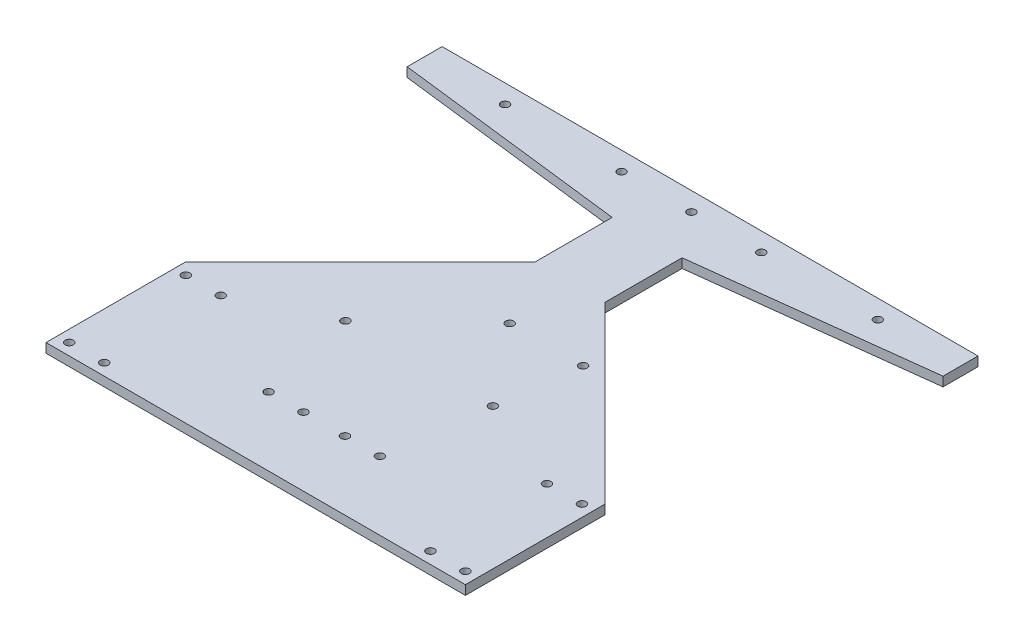
SolidWorks part; units mm, degrees
ref_plane "Front Plane" through (0, 0, 0) normal (0, 0, 1) x (1, 0, 0)
ref_plane "Top Plane" through (0, 0, 0) normal (0, 1, 0) x (1, 0, 0)
ref_plane "Right Plane" through (0, 0, 0) normal (1, 0, 0) x (0, 0, -1)
sketch "Sketch1" plane through (0, 0, 0) normal (0, 1, 0) x (1, 0, 0)
  line L0 (-90, 30) -> (-15, 105)
  line L2 (-90, 30) -> (-90, -30)
  line L3 (-90, -30) -> (90, -30)
  line L4 (90, 30) -> (90, -30)
  line L5 (-90, 30) -> (90, -30) construction
  line L6 (-90, -30) -> (90, 30) construction
  line L7 (90, 30) -> (15, 105)
  line L8 (15, 105) -> (15, 138)
  line L9 (15, 138) -> (115, 150)
  line L10 (115, 150) -> (115, 165)
  line L11 (115, 165) -> (-115, 165)
  line L12 (-115, 165) -> (-115, 150)
  line L13 (-115, 150) -> (-15, 138)
  line L14 (-15, 138) -> (-15, 105)
  line L15 (0, -55) -> (0, 55) construction
  line L16 (-55, 0) -> (55, 0) construction
  point P0 (0, 0)
  dimension "D1" = 60
  dimension "D2" = 180
  dimension "D3" = 100
  dimension "D4" = 15
  dimension "D5" = 15
  dimension "D6" = 15
  dimension "D7" = 138
  dimension "D8" = 150
extrude "Boss-Extrude1" add sketch "Sketch1" along normal blind 4
sketch "Sketch2" plane through (0, 4, 0) normal (0, 1, 0) x (1, 0, 0)
  line L0 (-90, 30) -> (90, 30) construction
  line L1 (90, 30) -> (89.7053, 30.6538) construction
  line L2 (89.7053, 30.6538) -> (90, -30) construction
  line L3 (90, -30) -> (-90, -30) construction
  line L4 (-90, -30) -> (-90, 30) construction
  line L5 (0, -2.2) -> (0, 2.2) construction
  line L6 (-2.2, 0) -> (2.2, 0) construction
  circle A2 centre (-85, 25) radius 1.75
  circle A4 centre (85, 25) radius 1.75
  circle A5 centre (85, -25) radius 1.75
  circle A6 centre (-85, -25) radius 1.75
  circle A7 centre (-70, 25) radius 1.75
  circle A8 centre (-70, -25) radius 1.75
  circle A9 centre (70, -25) radius 1.75
  circle A10 centre (70, 25) radius 1.75
  dimension "D2" = 3.5
  dimension "D1" = 85
  dimension "D3" = 25
  dimension "D4" = 15
extrude "Cut-Extrude1" cut sketch "Sketch2" against normal through all
sketch "Sketch3" plane through (0, 4, 0) normal (0, 1, 0) x (1, 0, 0)
  line L0 (0, 59.35) -> (37.85, 59.35) construction
  line L2 (37.85, 59.35) -> (37.85, 80.7) construction
  line L3 (37.85, 80.7) -> (-37.85, 80.7) construction
  line L5 (37.85, 38) -> (37.85, 80.7) construction
  line L6 (-37.85, 38) -> (-37.85, 80.7) construction
  line L7 (37.85, 38) -> (-37.85, 38) construction
  line L8 (-90, -30) -> (90, -30) construction
  line L9 (0, -2.2) -> (0, 2.2) construction
  circle A0 centre (2.4, 76.6) radius 1.75
  circle A1 centre (-33.8, 42.3) radius 1.75
  circle A2 centre (33.9, 76.6) radius 1.75
  circle A3 centre (29.5, 42.3) radius 1.75
  point P10 (0, 80.7)
  point P13 (-37.85, 59.35)
  dimension "D4" = 3.5
  dimension "D8" = 3.5
  dimension "D10" = 3.5
  dimension "D14" = 3.5
  dimension "D2" = 42.7
  dimension "D3" = 4.05
  dimension "D5" = 4.3
  dimension "D6" = 8.35
  dimension "D7" = 4.3
  dimension "D9" = 3.95
  dimension "D11" = 4.1
  dimension "D12" = 40.25
  dimension "D13" = 4.1
  dimension "D15" = 75.7
  dimension "D16" = 68
  dimension "D17" = 37.85
extrude "Cut-Extrude2" cut sketch "Sketch3" against normal through all
sketch "Sketch4" plane through (0, 4, 0) normal (0, 1, 0) x (1, 0, 0)
  line L0 (0, 0) -> (-32.8, 0) construction
  line L1 (-2.2, 0) -> (2.2, 0) construction
  line L2 (-32.8, 0) -> (-32.8, -30) construction
  line L3 (-90, -30) -> (90, -30) construction
  line L4 (-32.8, -30) -> (32.8, -30) construction
  line L5 (32.8, -30) -> (32.8, 0) construction
  line L6 (-32.8, 0) -> (-32.8, 28.8) construction
  line L7 (-32.8, 28.8) -> (32.8, 28.8) construction
  line L8 (32.8, 28.8) -> (32.8, 0) construction
  line L9 (0, -2.2) -> (0, 2.2) construction
  circle A0 centre (-23.9, -0.6) radius 1.75
  circle A1 centre (-8.9, -0.6) radius 1.75
  circle A2 centre (8.9, -0.6) radius 1.75
  circle A3 centre (23.9, -0.6) radius 1.75
  dimension "D5" = 3.5
  dimension "D1" = 32.8
  dimension "D2" = 65.6
  dimension "D3" = 28.8
  dimension "D4" = 29.4
  dimension "D6" = 15
  dimension "D7" = 15
  dimension "D8" = 8.9
  dimension "D9" = 8.9
extrude "Cut-Extrude3" cut sketch "Sketch4" against normal through all
sketch "Sketch5" plane through (0, 4, 0) normal (0, 1, 0) x (1, 0, 0)
  line L0 (0, -2.2) -> (0, 2.2) construction
  line L1 (115, 165) -> (-115, 165) construction
  circle A0 centre (0, 157) radius 1.75
  circle A1 centre (-30, 157) radius 1.75
  circle A2 centre (30, 157) radius 1.75
  circle A3 centre (80, 157) radius 1.75
  circle A4 centre (-80, 157) radius 1.75
  dimension "D1" = 3.5
  dimension "D2" = 8
  dimension "D3" = 60
  dimension "D4" = 50
  dimension "30" = 30
  dimension "D5" = 50
extrude "Cut-Extrude4" cut sketch "Sketch5" against normal through all
